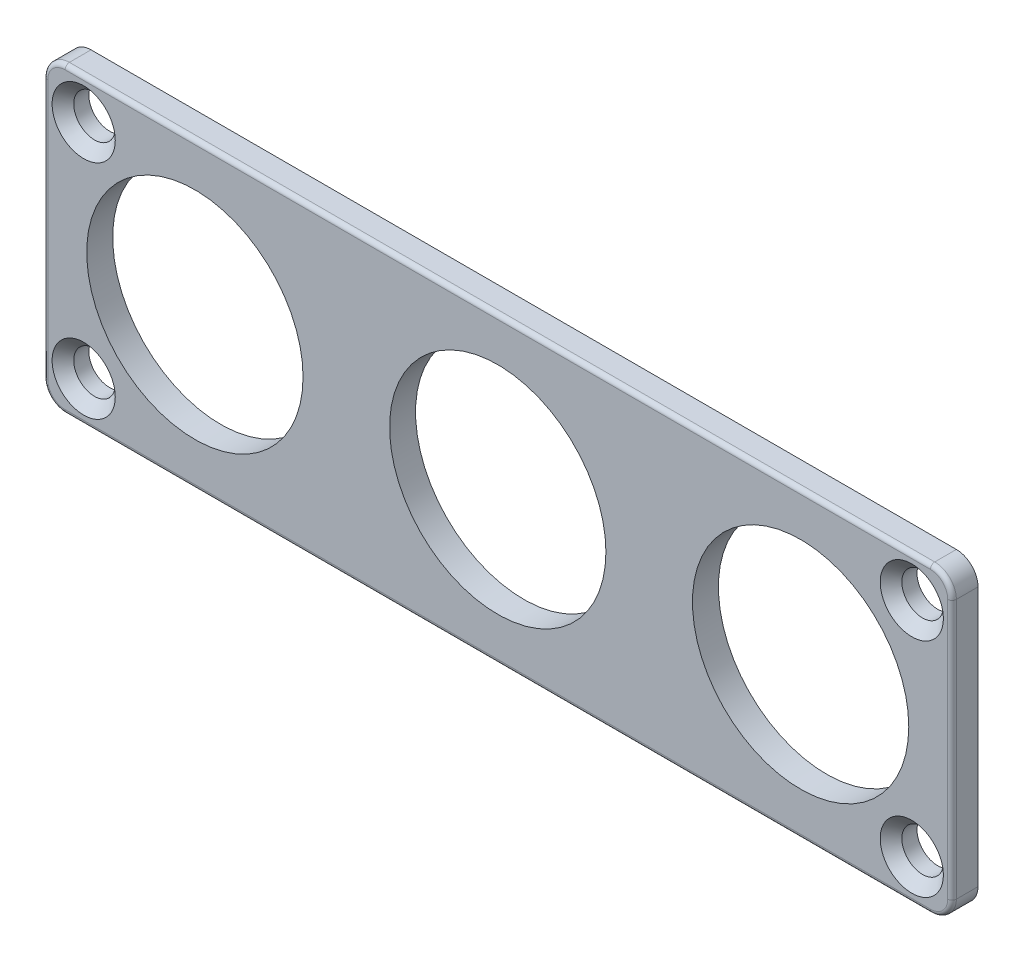
SolidWorks part; units mm, degrees
material "PPE"
ref_plane "Front Plane" through (0, 0, 0) normal (0, 0, 1) x (1, 0, 0)
ref_plane "Top Plane" through (0, 0, 0) normal (0, 1, 0) x (1, 0, 0)
ref_plane "Right Plane" through (0, 0, 0) normal (1, 0, 0) x (0, 0, -1)
sketch "Sketch1" plane through (0, 0, 0) normal (0, 0, 1) x (1, 0, 0)
  line L0 (-13.8111, 3.9688) -> (-20.3306, -2.5504) construction
  line L1 (3.9688, 3.9688) -> (-3.9688, -3.9688) construction
  line L2 (20.3311, 2.5506) -> (13.8114, -3.9688) construction
  line L3 (-13.8111, -3.9688) -> (-20.3306, 2.5506) construction
  line L4 (3.9688, -3.9688) -> (-3.9688, 3.9688) construction
  line L5 (20.3311, -2.5504) -> (13.8114, 3.9688) construction
  line L6 (-26.6699, -7.6202) -> (-26.6699, 7.62)
  line L7 (-18.4147, -4.9606) -> (-18.4147, 3.5858)
  line L8 (-17.7798, -6.1454) -> (-17.7802, 6.145) construction
  line L9 (0, -9.7791) -> (0, 9.7791) construction
  line L10 (-15.4875, 6.8883) -> (-15.8082, 5.9245) construction
  line L11 (-20.0725, -6.8885) -> (-19.7514, -5.9249) construction
  line L12 (-20.0725, 6.8883) -> (-19.7514, 5.9245) construction
  line L13 (-15.4875, -6.8885) -> (-15.8082, -5.9249) construction
  line L14 (-9.1671, -8.4122) -> (-9.1671, 8.4121) construction
  line L15 (-8.8897, -7.6202) -> (-8.8897, 7.62) construction
  line L16 (-8.6124, -8.4122) -> (-8.6124, 8.4121) construction
  line L17 (25.4002, -8.8901) -> (10.1603, -8.8901)
  line L18 (7.6202, -8.8901) -> (-7.6199, -8.8901)
  line L19 (-10.1599, -8.8901) -> (-25.4, -8.8901)
  line L20 (-18.4147, -4.9606) -> (-17.5227, -5.3184) construction
  line L21 (22.7416, -0.6349) -> (12.8202, -0.6349)
  line L22 (11.6351, 0) -> (23.9249, -0.0003) construction
  line L23 (12.8202, 0.6351) -> (22.7416, 0.6351)
  line L24 (24.6694, 2.2924) -> (23.7048, 1.9716) construction
  line L27 (24.6689, -2.2925) -> (23.7622, -1.9911) construction
  line L28 (10.8916, 2.2924) -> (11.8559, 1.9716) construction
  line L29 (8.6127, -8.4122) -> (8.6127, 8.4121) construction
  line L30 (8.8901, -7.6202) -> (8.8901, 7.62) construction
  line L31 (9.1674, -8.4122) -> (9.1674, 8.4121) construction
  line L32 (-25.4, 8.8901) -> (-10.1599, 8.8901)
  line L33 (-7.6199, 8.8901) -> (7.6202, 8.8901)
  line L34 (10.1603, 8.8901) -> (25.4002, 8.8901)
  line L35 (12.8202, -0.6349) -> (12.8202, 0.6351) construction
  line L36 (22.7416, -0.6349) -> (22.7416, 0.6351) construction
  line L37 (26.6701, 7.62) -> (26.6701, -7.6202)
  spline S0 degree 3 poles (-17.7798, -6.1454) (-17.261, -6.8685) (-16.3318, -7.1696) (-15.4871, -6.8892) knots 0 0 0 0 1 1 1 1 construction
  spline S1 degree 3 poles (-26.3312, -6.5192) (-26.3312, -7.6419) (-25.4214, -8.5511) (-24.2993, -8.5511) (-23.1769, -8.5511) (-22.267, -7.6419) (-22.267, -6.5192) knots 2 2 2 2 3 3 3 4 4 4 4
  spline S2 degree 3 poles (-22.267, -6.5192) (-22.267, -5.3971) (-23.1769, -4.4872) (-24.2993, -4.4872) (-25.4214, -4.4872) (-26.3312, -5.3971) (-26.3312, -6.5192) knots 0 0 0 0 1 1 1 2 2 2 2
  spline S3 degree 3 poles (-20.0725, -6.8885) (-19.2281, -7.1696) (-18.2986, -6.8685) (-17.7798, -6.1454) knots 0 0 0 0 1 1 1 1 construction
  spline S4 degree 3 poles (-8.8897, -7.6202) (-8.8897, -8.3216) (-8.3213, -8.8901) (-7.6199, -8.8901) knots 0 0 0 0 1 1 1 1
  spline S5 degree 3 poles (-10.1599, -8.8901) (-9.4585, -8.8901) (-8.8897, -8.3216) (-8.8897, -7.6202) knots 0 0 0 0 1 1 1 1
  spline S6 degree 3 poles (-26.6699, -7.6202) (-26.6699, -8.3216) (-26.1011, -8.8901) (-25.4, -8.8901) knots 0 0 0 0 1 1 1 1
  spline S7 degree 3 poles (-25.3787, -6.5192) (-25.3787, -7.1155) (-24.8953, -7.5989) (-24.2993, -7.5989) (-23.703, -7.5989) (-23.2196, -7.1155) (-23.2196, -6.5192) knots 2 2 2 2 3 3 3 4 4 4 4
  spline S8 degree 3 poles (-23.2196, -6.5192) (-23.2196, -5.9232) (-23.703, -5.4398) (-24.2993, -5.4398) (-24.8953, -5.4398) (-25.3787, -5.9232) (-25.3787, -6.5192) knots 0 0 0 0 1 1 1 2 2 2 2
  spline S9 degree 3 poles (-18.8364, -5.7847) (-18.5718, -5.5938) (-18.4147, -5.2872) (-18.4147, -4.9606) knots 0 0 0 0 1 1 1 1
  spline S10 degree 3 poles (-19.7514, -5.9249) (-19.4417, -6.0279) (-19.1013, -5.9755) (-18.8364, -5.7847) knots 0 0 0 0 1 1 1 1
  spline S11 degree 3 poles (-16.7232, -5.7847) (-16.4587, -5.9755) (-16.1183, -6.0279) (-15.8082, -5.9249) knots 0 0 0 0 1 1 1 1
  spline S13 degree 3 poles (-6.8154, -6.5192) (-6.8154, -7.0104) (-6.4175, -7.4083) (-5.9266, -7.4083) (-5.4353, -7.4083) (-5.0374, -7.0104) (-5.0374, -6.5192) knots 2 2 2 2 3 3 3 4 4 4 4 construction
  spline S14 degree 3 poles (-5.0374, -6.5192) (-5.0374, -6.0286) (-5.4353, -5.6307) (-5.9266, -5.6307) (-6.4175, -5.6307) (-6.8154, -6.0286) (-6.8154, -6.5192) knots 0 0 0 0 1 1 1 2 2 2 2 construction
  spline S15 degree 3 poles (-12.742, -6.5192) (-12.742, -7.0104) (-12.3441, -7.4083) (-11.8532, -7.4083) (-11.3619, -7.4083) (-10.964, -7.0104) (-10.964, -6.5192) knots 2 2 2 2 3 3 3 4 4 4 4 construction
  spline S16 degree 3 poles (-10.964, -6.5192) (-10.964, -6.0286) (-11.3619, -5.6307) (-11.8532, -5.6307) (-12.3441, -5.6307) (-12.742, -6.0286) (-12.742, -6.5192) knots 0 0 0 0 1 1 1 2 2 2 2 construction
  spline S17 degree 3 poles (-15.4875, 6.8883) (-12.5213, 5.9013) (-10.52, 3.1261) (-10.52, 0) knots 0 0 0 0 1 1 1 1 construction
  spline S18 degree 3 poles (-10.52, 0) (-10.52, -3.1264) (-12.5213, -5.9018) (-15.4875, -6.8885) knots 0 0 0 0 1 1 1 1 construction
  spline S19 degree 3 poles (-25.04, 0) (-25.04, -3.1264) (-23.0387, -5.9018) (-20.0725, -6.8885) knots 0 0 0 0 1 1 1 1 construction
  spline S20 degree 3 poles (-20.0725, 6.8883) (-23.0387, 5.9013) (-25.04, 3.1261) (-25.04, 0) knots 0 0 0 0 1 1 1 1 construction
  spline S21 degree 3 poles (-15.8082, 5.9245) (-13.2571, 5.0755) (-11.536, 2.6886) (-11.536, 0) knots 0 0 0 0 1 1 1 1
  spline S22 degree 3 poles (-11.536, 0) (-11.536, -2.6889) (-13.2571, -5.0757) (-15.8082, -5.9249) knots 0 0 0 0 1 1 1 1
  spline S23 degree 3 poles (-24.024, 0) (-24.024, -2.6889) (-22.3029, -5.0757) (-19.7514, -5.9249) knots 0 0 0 0 1 1 1 1
  spline S24 degree 3 poles (-19.7514, 5.9245) (-22.3029, 5.0755) (-24.024, 2.6886) (-24.024, 0) knots 0 0 0 0 1 1 1 1
  spline S25 degree 3 poles (-17.7802, 6.145) (-18.299, 6.8683) (-19.2285, 7.1699) (-20.0729, 6.8886) knots 0 0 0 0 1 1 1 1 construction
  spline S26 degree 3 poles (-26.3312, 6.5193) (-26.3312, 5.3967) (-25.4214, 4.4874) (-24.2993, 4.4874) (-23.1769, 4.4874) (-22.267, 5.3967) (-22.267, 6.5193) knots 2 2 2 2 3 3 3 4 4 4 4
  spline S27 degree 3 poles (-22.267, 6.5193) (-22.267, 7.6416) (-23.1769, 8.5514) (-24.2993, 8.5514) (-25.4214, 8.5514) (-26.3312, 7.6416) (-26.3312, 6.5193) knots 0 0 0 0 1 1 1 2 2 2 2
  spline S28 degree 3 poles (-15.4875, 6.8883) (-16.3322, 7.1696) (-17.2614, 6.8683) (-17.7802, 6.145) knots 0 0 0 0 1 1 1 1 construction
  spline S29 degree 3 poles (-7.6199, 8.8901) (-8.3213, 8.8901) (-8.8897, 8.3213) (-8.8897, 7.62) knots 0 0 0 0 1 1 1 1
  spline S30 degree 3 poles (-25.4, 8.8901) (-26.1011, 8.8901) (-26.6699, 8.3213) (-26.6699, 7.62) knots 0 0 0 0 1 1 1 1
  spline S31 degree 3 poles (-8.8897, 7.62) (-8.8897, 8.3213) (-9.4585, 8.8901) (-10.1599, 8.8901) knots 0 0 0 0 1 1 1 1
  spline S34 degree 3 poles (-18.8364, 5.7845) (-19.1013, 5.9757) (-19.4417, 6.0275) (-19.7514, 5.9245) knots 0 0 0 0 1 1 1 1
  spline S35 degree 3 poles (-18.4147, 3.5858) (-18.1937, 4.3446) (-18.3512, 5.1624) (-18.8364, 5.7845) knots 0 0 0 0 1 1 1 1
  spline S36 degree 3 poles (-12.742, 6.5193) (-12.742, 6.0282) (-12.3441, 5.6303) (-11.8532, 5.6303) (-11.3619, 5.6303) (-10.964, 6.0282) (-10.964, 6.5193) knots 2 2 2 2 3 3 3 4 4 4 4 construction
  spline S37 degree 3 poles (-10.964, 6.5193) (-10.964, 7.0101) (-11.3619, 7.408) (-11.8532, 7.408) (-12.3441, 7.408) (-12.742, 7.0101) (-12.742, 6.5193) knots 0 0 0 0 1 1 1 2 2 2 2 construction
  spline S38 degree 3 poles (-6.8154, 6.5193) (-6.8154, 6.0282) (-6.4175, 5.6303) (-5.9266, 5.6303) (-5.4353, 5.6303) (-5.0374, 6.0282) (-5.0374, 6.5193) knots 2 2 2 2 3 3 3 4 4 4 4 construction
  spline S39 degree 3 poles (-5.0374, 6.5193) (-5.0374, 7.0101) (-5.4353, 7.408) (-5.9266, 7.408) (-6.4175, 7.408) (-6.8154, 7.0101) (-6.8154, 6.5193) knots 0 0 0 0 1 1 1 2 2 2 2 construction
  spline S40 degree 3 poles (11.6351, 0) (10.912, -0.5188) (10.6105, -1.448) (10.8916, -2.2931) knots 0 0 0 0 1 1 1 1 construction
  spline S41 degree 3 poles (22.2672, -6.5192) (22.2672, -7.6419) (23.1774, -8.5511) (24.2998, -8.5511) (25.4215, -8.5511) (26.3317, -7.6419) (26.3317, -6.5192) knots 2 2 2 2 3 3 3 4 4 4 4
  spline S42 degree 3 poles (26.3317, -6.5192) (26.3317, -5.3971) (25.4215, -4.4872) (24.2998, -4.4872) (23.1774, -4.4872) (22.2672, -5.3971) (22.2672, -6.5192) knots 0 0 0 0 1 1 1 2 2 2 2
  spline S43 degree 3 poles (23.9249, -0.0003) (24.6478, -0.519) (24.9498, -1.4477) (24.6689, -2.2925) knots 0 0 0 0 1 1 1 1 construction
  spline S44 degree 3 poles (25.4002, -8.8901) (26.1016, -8.8901) (26.6701, -8.3216) (26.6701, -7.6202) knots 0 0 0 0 1 1 1 1
  spline S45 degree 3 poles (8.8901, -7.6202) (8.8901, -8.3216) (9.4589, -8.8901) (10.1603, -8.8901) knots 0 0 0 0 1 1 1 1
  spline S46 degree 3 poles (7.6202, -8.8901) (8.3216, -8.8901) (8.8901, -8.3216) (8.8901, -7.6202) knots 0 0 0 0 1 1 1 1
  spline S47 degree 3 poles (23.2201, -6.5192) (23.2201, -7.1155) (23.7031, -7.5989) (24.2998, -7.5989) (24.8958, -7.5989) (25.3788, -7.1155) (25.3788, -6.5192) knots 2 2 2 2 3 3 3 4 4 4 4
  spline S48 degree 3 poles (25.3788, -6.5192) (25.3788, -5.9232) (24.8958, -5.4398) (24.2998, -5.4398) (23.7031, -5.4398) (23.2201, -5.9232) (23.2201, -6.5192) knots 0 0 0 0 1 1 1 2 2 2 2
  spline S49 degree 3 poles (22.7416, -0.6349) (23.0672, -0.6485) (23.367, -0.8182) (23.5474, -1.0908) knots 0 0 0 0 1 1 1 1
  spline S50 degree 3 poles (23.5474, -1.0908) (23.7596, -1.3389) (23.8395, -1.6738) (23.7622, -1.9911) knots 0 0 0 0 1 1 1 1
  spline S51 degree 3 poles (11.9997, -1.0639) (11.814, -1.3327) (11.769, -1.674) (11.8783, -1.9816) knots 0 0 0 0 1 1 1 1
  spline S52 degree 3 poles (12.8202, -0.6349) (12.4933, -0.6377) (12.1883, -0.7973) (11.9997, -1.0639) knots 0 0 0 0 1 1 1 1
  spline S53 degree 3 poles (5.0378, -6.5192) (5.0378, -7.0104) (5.4357, -7.4083) (5.9269, -7.4083) (6.4179, -7.4083) (6.8158, -7.0104) (6.8158, -6.5192) knots 2 2 2 2 3 3 3 4 4 4 4 construction
  spline S54 degree 3 poles (6.8158, -6.5192) (6.8158, -6.0286) (6.4179, -5.6307) (5.9269, -5.6307) (5.4357, -5.6307) (5.0378, -6.0286) (5.0378, -6.5192) knots 0 0 0 0 1 1 1 2 2 2 2 construction
  spline S55 degree 3 poles (10.9644, -6.5192) (10.9644, -7.0104) (11.3626, -7.4083) (11.8535, -7.4083) (12.3445, -7.4083) (12.7424, -7.0104) (12.7424, -6.5192) knots 2 2 2 2 3 3 3 4 4 4 4 construction
  spline S56 degree 3 poles (12.7424, -6.5192) (12.7424, -6.0286) (12.3445, -5.6307) (11.8535, -5.6307) (11.3626, -5.6307) (10.9644, -6.0286) (10.9644, -6.5192) knots 0 0 0 0 1 1 1 2 2 2 2 construction
  spline S57 degree 3 poles (-7.2599, 0) (-7.2599, -4.0097) (-4.0094, -7.2602) (0, -7.2602) (4.0097, -7.2602) (7.2602, -4.0097) (7.2602, 0) knots 2 2 2 2 3 3 3 4 4 4 4 construction
  spline S58 degree 3 poles (7.2602, 0) (7.2602, 4.0097) (4.0097, 7.2602) (0, 7.2602) (-4.0094, 7.2602) (-7.2599, 4.0097) (-7.2599, 0) knots 0 0 0 0 1 1 1 2 2 2 2 construction
  spline S59 degree 3 poles (17.7799, -7.2602) (14.6534, -7.26) (11.879, -5.2589) (10.8915, -2.2923) knots 0 0 0 0 1 1 1 1 construction
  spline S60 degree 3 poles (17.78, -6.2446) (15.0913, -6.2444) (12.7048, -4.5231) (11.8558, -1.9716) knots 0 0 0 0 1 1 1 1
  spline S61 degree 3 poles (17.7803, 7.2599) (14.6538, 7.2598) (11.8792, 5.2589) (10.8916, 2.2924) knots 0 0 0 0 1 1 1 1 construction
  spline S62 degree 3 poles (24.6694, 2.2924) (23.682, 5.259) (20.9065, 7.2599) (17.7803, 7.2599) knots 0 0 0 0 1 1 1 1 construction
  spline S63 degree 3 poles (23.7047, -1.9723) (22.8556, -4.5238) (20.4686, -6.2448) (17.78, -6.2446) knots 0 0 0 0 1 1 1 1
  spline S64 degree 3 poles (24.6693, -2.2931) (23.6817, -5.2597) (20.9061, -7.2604) (17.7799, -7.2602) knots 0 0 0 0 1 1 1 1 construction
  spline S65 degree 3 poles (17.7803, 6.2442) (15.0917, 6.2442) (12.705, 4.523) (11.8559, 1.9716) knots 0 0 0 0 1 1 1 1
  spline S66 degree 3 poles (23.7048, 1.9716) (22.8558, 4.5231) (20.469, 6.2443) (17.7803, 6.2442) knots 0 0 0 0 1 1 1 1
  spline S67 degree 3 poles (24.6694, 2.2924) (24.9502, 1.4473) (24.6479, 0.5183) (23.9249, -0.0003) knots 0 0 0 0 1 1 1 1 construction
  spline S68 degree 3 poles (22.2672, 6.5193) (22.2672, 5.3967) (23.1774, 4.4874) (24.2998, 4.4874) (25.4215, 4.4874) (26.3317, 5.3967) (26.3317, 6.5193) knots 2 2 2 2 3 3 3 4 4 4 4
  spline S69 degree 3 poles (26.3317, 6.5193) (26.3317, 7.6416) (25.4215, 8.5514) (24.2998, 8.5514) (23.1774, 8.5514) (22.2672, 7.6416) (22.2672, 6.5193) knots 0 0 0 0 1 1 1 2 2 2 2
  spline S70 degree 3 poles (10.8916, 2.2924) (10.6109, 1.4478) (10.9123, 0.519) (11.6354, 0) knots 0 0 0 0 1 1 1 1 construction
  spline S71 degree 3 poles (8.8901, 7.62) (8.8901, 8.3213) (8.3216, 8.8901) (7.6202, 8.8901) knots 0 0 0 0 1 1 1 1
  spline S72 degree 3 poles (10.1603, 8.8901) (9.4589, 8.8901) (8.8901, 8.3213) (8.8901, 7.62) knots 0 0 0 0 1 1 1 1
  spline S73 degree 3 poles (26.6701, 7.62) (26.6701, 8.3213) (26.1016, 8.8901) (25.4002, 8.8901) knots 0 0 0 0 1 1 1 1
  spline S74 degree 3 poles (23.2201, 6.5193) (23.2201, 5.9232) (23.7031, 5.4398) (24.2998, 5.4398) (24.8958, 5.4398) (25.3788, 5.9232) (25.3788, 6.5193) knots 2 2 2 2 3 3 3 4 4 4 4
  spline S75 degree 3 poles (25.3788, 6.5193) (25.3788, 7.1155) (24.8958, 7.5989) (24.2998, 7.5989) (23.7031, 7.5989) (23.2201, 7.1155) (23.2201, 6.5193) knots 0 0 0 0 1 1 1 2 2 2 2
  spline S76 degree 3 poles (23.7048, 1.9716) (23.8082, 1.6619) (23.7565, 1.3215) (23.5656, 1.0566) knots 0 0 0 0 1 1 1 1
  spline S77 degree 3 poles (23.5656, 1.0566) (23.3741, 0.7917) (23.0675, 0.6351) (22.7416, 0.6351) knots 0 0 0 0 1 1 1 1
  spline S78 degree 3 poles (11.9961, 1.0566) (12.187, 0.7917) (12.4933, 0.6351) (12.8202, 0.6351) knots 0 0 0 0 1 1 1 1
  spline S79 degree 3 poles (11.8559, 1.9716) (11.7529, 1.6619) (11.8049, 1.3215) (11.9961, 1.0566) knots 0 0 0 0 1 1 1 1
  spline S80 degree 3 poles (10.9644, 6.5193) (10.9644, 6.0282) (11.3626, 5.6303) (11.8535, 5.6303) (12.3445, 5.6303) (12.7424, 6.0282) (12.7424, 6.5193) knots 2 2 2 2 3 3 3 4 4 4 4 construction
  spline S81 degree 3 poles (12.7424, 6.5193) (12.7424, 7.0101) (12.3445, 7.408) (11.8535, 7.408) (11.3626, 7.408) (10.9644, 7.0101) (10.9644, 6.5193) knots 0 0 0 0 1 1 1 2 2 2 2 construction
  spline S82 degree 3 poles (5.0378, 6.5193) (5.0378, 6.0282) (5.4357, 5.6303) (5.9269, 5.6303) (6.4179, 5.6303) (6.8158, 6.0282) (6.8158, 6.5193) knots 2 2 2 2 3 3 3 4 4 4 4 construction
  spline S83 degree 3 poles (6.8158, 6.5193) (6.8158, 7.0101) (6.4179, 7.408) (5.9269, 7.408) (5.4357, 7.408) (5.0378, 7.0101) (5.0378, 6.5193) knots 0 0 0 0 1 1 1 2 2 2 2 construction
  spline S84 degree 3 poles (-6.2439, 0) (-6.2439, -3.4489) (-3.4482, -6.2442) (0, -6.2442) (3.4489, -6.2442) (6.2442, -3.4489) (6.2442, 0) knots 2 2 2 2 3 3 3 4 4 4 4
  spline S85 degree 3 poles (6.2442, 0) (6.2442, 3.4484) (3.4489, 6.2442) (0, 6.2442) (-3.4482, 6.2442) (-6.2439, 3.4484) (-6.2439, 0) knots 0 0 0 0 1 1 1 2 2 2 2
  point P18 (-17.78, -0.0002)
  point P86 (17.78, -0.0002)
  point P123 (0, 0)
  dimension "D1" = 17.78
  dimension "D2" = 17.78
sketch "Sketch2" plane through (0, 0, 0) normal (0, 0, 1) x (1, 0, 0)
  line L0 (-7.6199, 8.8901) -> (7.6202, 8.8901) construction
  line L1 (26.67, -8.8901) -> (-26.67, -8.8901)
  line L2 (26.67, -8.8901) -> (26.67, 8.8901)
  line L3 (26.67, 8.8901) -> (-26.67, 8.8901)
  line L4 (-26.67, -8.8901) -> (-26.67, 8.8901)
  line L5 (26.67, -8.8901) -> (-26.67, 8.8901) construction
  line L6 (26.67, 8.8901) -> (-26.67, -8.8901) construction
  point P0 (0, 0)
  dimension "D1" = 53.34
  dimension "D2" = 17.7801
extrude "Boss-Extrude1" add sketch "Sketch2" against normal blind 1.524
hole_wizard "#2 Clearance Hole1" positions "Sketch5" profile "Sketch4" hole size "#2" standard "Ansi Inch" end condition up to next
sketch "Sketch5" plane through (0, 0, 0) normal (0, 0, 1) x (1, 0, 0)
  line L0 (0, 0) -> (0, 12.8116) construction
  line L2 (0, 0) -> (31.8211, 0) construction
  line L4 (-12.742, 6.5193) -> (-15.3484, 6.5193) construction
  line L6 (-26.6699, -7.6202) -> (-26.6699, 7.62) construction
  point P0 (-24.3077, 6.5193)
  point P1 (-24.3077, -6.5193)
  point P3 (24.3077, -6.5193)
  point P5 (24.3077, 6.5193)
  dimension "D1" = 2.3622
sketch "Sketch4" plane through (-24.3077, 6.5193, 0) normal (1, 0, 0) x (0, -1, 0)
  line L0 (0, 0) -> (0, 1.524)
  line L1 (0, 1.524) -> (1.2192, 1.524)
  line L2 (1.2192, 1.524) -> (1.2192, 0.635)
  line L3 (1.2192, 0.635) -> (1.8542, 0)
  line L5 (1.8542, 0) -> (0, 0)
  line L6 (-1.2192, 0.635) -> (-1.8542, 0) construction
  line L11 (0, -6.35) -> (0, 107.95) construction
  dimension "Thru Hole Dia." = 2.4384
  dimension "Thru Hole Depth" = 1.524
  dimension "Near C'Sink Dia." = 3.7084
  dimension "Near C'Sink Angle" = 90
fillet "Fillet1" radius 1.27 4 edges at (-26.67, 8.8901, -0.762) (26.67, 8.8901, -0.762) (26.67, -8.8901, -0.762) (-26.67, -8.8901, -0.762)
sketch "Sketch6" plane through (0, 0, 0) normal (0, 0, 1) x (1, 0, 0)
  line L0 (0.8382, 0) -> (-0.8382, 0) construction
  line L1 (11.6351, 0) -> (23.9249, -0.0003) construction
  circle A0 centre (0, 0) radius 6.35
  circle A1 centre (-17.78, 0) radius 6.35
  circle A2 centre (17.78, -0.0002) radius 6.35
  dimension "D1" = 12.7
  dimension "D2" = 17.78
  dimension "D3" = 17.78
extrude "Cut-Extrude1" cut sketch "Sketch6" against normal up to next
fillet "Fillet2" radius 0.254 8 edges at (-26.298, -8.5181, 0) (-26.67, 0, 0) (-26.298, 8.5181, 0) (0, 8.8901, 0) (26.298, 8.5181, 0) (26.67, 0, 0) (26.298, -8.5181, 0) (0, -8.8901, 0)
